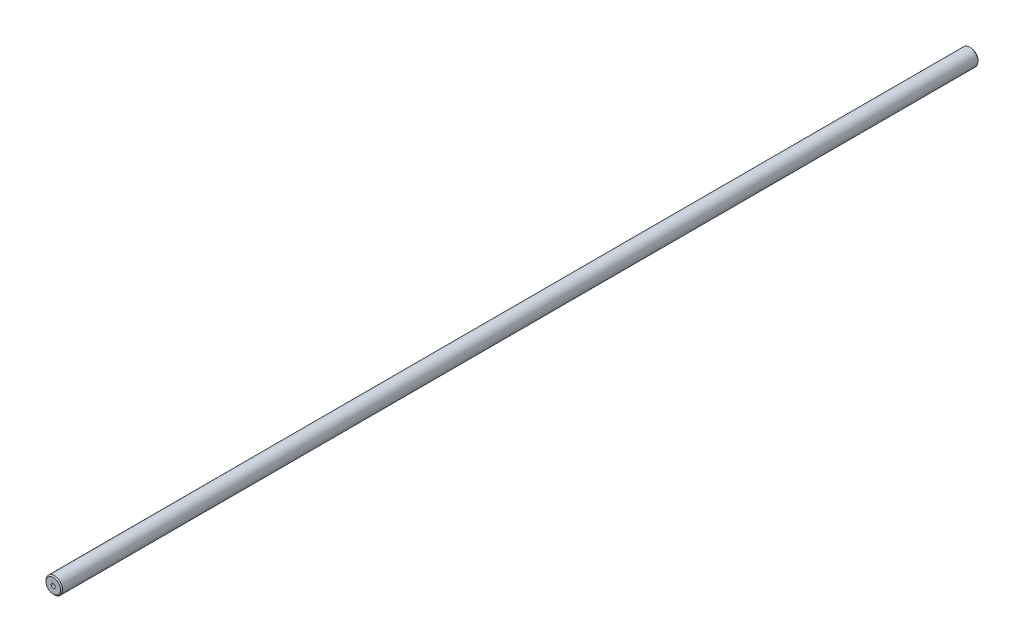
SolidWorks part; units mm, degrees
ref_plane "Front Plane" through (0, 0, 0) normal (0, 0, 1) x (1, 0, 0)
ref_plane "Top Plane" through (0, 0, 0) normal (0, 1, 0) x (1, 0, 0)
ref_plane "Right Plane" through (0, 0, 0) normal (1, 0, 0) x (0, 0, -1)
sketch "Sketch1" plane through (0, 0, 0) normal (0, 0, 1) x (1, 0, 0)
  circle A0 centre (0, 0) radius 4
  dimension "D1" = 8
extrude "Boss-Extrude1" add sketch "Sketch1" along normal blind 441
sketch "Sketch2" plane through (0, 0, 441) normal (0, 0, 1) x (1, 0, 0)
  circle A0 centre (0, 0) radius 1
  dimension "D1" = 2
extrude "Cut-Extrude1" cut sketch "Sketch2" against normal blind 10
chamfer "Chamfer1" distance 0.5 angle 45 2 edges at (4, 0, 0) (4, 0, 441)
